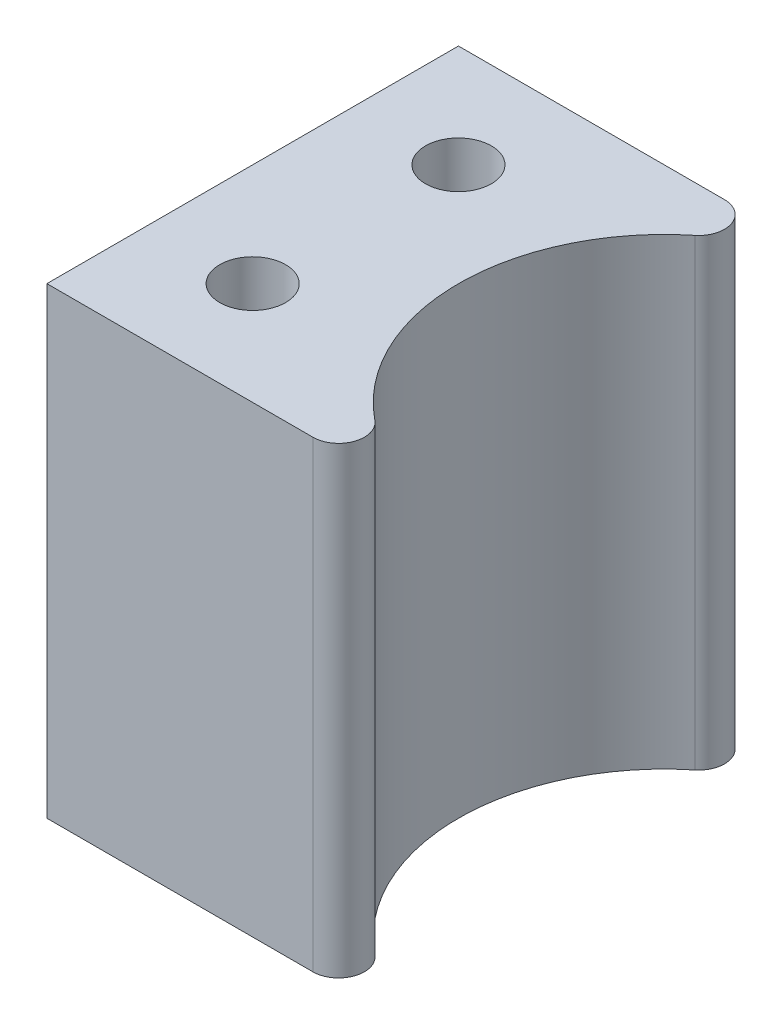
SolidWorks part; units mm, degrees
material "Polyurethane Foam Rigid"
ref_plane "Front Plane" through (0, 0, 0) normal (0, 0, 1) x (1, 0, 0)
ref_plane "Top Plane" through (0, 0, 0) normal (0, 1, 0) x (1, 0, 0)
ref_plane "Right Plane" through (0, 0, 0) normal (1, 0, 0) x (0, 0, -1)
sketch "Sketch3" plane through (0, 0, 0) normal (0, 1, 0) x (1, 0, 0)
  line L0 (-27.7812, 0) -> (-27.7812, 25.4)
  line L1 (-27.7812, 25.4) -> (-11.3615, 25.4)
  line L2 (-27.7812, 12.7) -> (-21.4312, 12.7) construction
  line L3 (-27.7812, 0) -> (-11.3615, 0)
  line L4 (-21.4312, 12.7) -> (-21.4312, 25.4) construction
  line L5 (-21.4312, 12.7) -> (-21.4312, 0) construction
  arc A0 (-11.3615, 0) -> (-10.3637, 2.8222) centre (-11.3615, 1.5875) ccw
  arc A1 (-11.3615, 25.4) -> (-10.3637, 22.5778) centre (-11.3615, 23.8125) cw
  arc A2 (-10.3637, 22.5778) -> (-10.3637, 2.8222) centre (-2.3813, 12.7) ccw
  circle A3 centre (-21.4312, 6.35) radius 2.032
  circle A4 centre (-21.4312, 19.05) radius 2.032
  point P10 (-21.4312, 19.05)
  point P18 (-21.4312, 6.35)
extrude "Boss-Extrude1" add sketch "Sketch3" along normal blind 28.575
